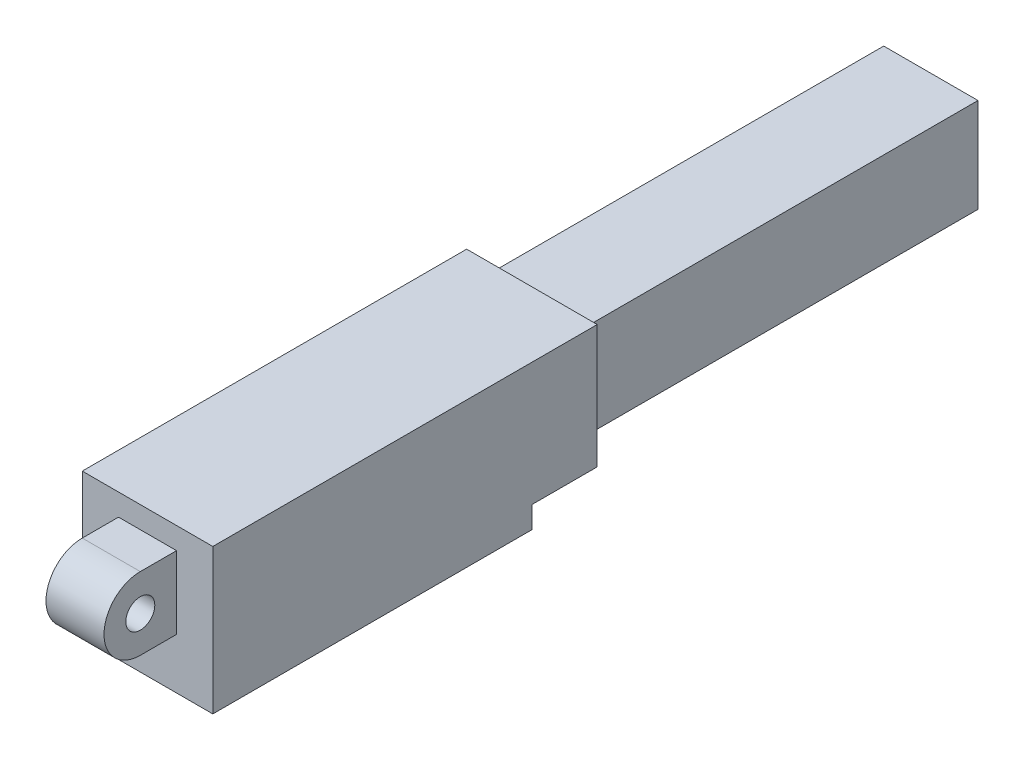
SolidWorks part; units mm, degrees
ref_plane "Front Plane" through (0, 0, 0) normal (0, 0, 1) x (1, 0, 0)
ref_plane "Top Plane" through (0, 0, 0) normal (0, 1, 0) x (1, 0, 0)
ref_plane "Right Plane" through (0, 0, 0) normal (1, 0, 0) x (0, 0, -1)
sketch "Sketch1" plane through (0, 0, 0) normal (1, 0, 0) x (0, 0, -1)
  line L0 (-26.5, 10) -> (26.5, 10)
  line L1 (26.5, 10) -> (26.5, -7)
  line L2 (26.5, -7) -> (17.5, -7)
  line L3 (17.5, -7) -> (17.5, -10)
  line L4 (17.5, -10) -> (-26.5, -10)
  line L5 (-26.5, -10) -> (-26.5, 10)
  line L6 (-26.5, -10) -> (26.5, 10) construction
  point P2 (0, 0)
  dimension "D1" = 53
  dimension "D2" = 20
  dimension "D3" = 9
  dimension "D4" = 3
extrude "Boss-Extrude1" add sketch "Sketch1" along normal mid plane 18
sketch "Sketch2" plane through (0, 0, 0) normal (1, 0, 0) x (0, 0, -1)
  line L0 (-31.5, 7) -> (-26.5, 7)
  line L1 (-26.5, 10) -> (-26.5, -10) construction
  line L2 (-26.5, 7) -> (-26.5, -3)
  line L3 (-26.5, -3) -> (-31.5, -3)
  line L4 (26.5, 10) -> (-26.5, 10) construction
  circle A0 centre (-31.5, 2) radius 2
  arc A1 (-31.5, 7) -> (-31.5, -3) centre (-31.5, 2) ccw
  dimension "D2" = 4
  dimension "D3" = 10
  dimension "D1" = 3
  dimension "D4" = 5
extrude "Boss-Extrude2" add sketch "Sketch2" along normal mid plane 8
sketch "Sketch3" plane through (0, 0, -26.5) normal (0, 0, -1) x (-1, 0, 0)
  line L0 (9, -7) -> (9, 10) construction
  line L1 (-6.5, -5) -> (6.5, -5)
  line L2 (-6.5, -5) -> (-6.5, 8)
  line L3 (-6.5, 8) -> (6.5, 8)
  line L4 (6.5, -5) -> (6.5, 8)
  line L5 (-6.5, -5) -> (6.5, 8) construction
  line L6 (-6.5, 8) -> (6.5, -5) construction
  line L7 (-9, 10) -> (9, 10) construction
  line L8 (-9, -7) -> (9, -7) construction
  point P0 (0, 1.5)
  dimension "D1" = 2.5
  dimension "D2" = 2
  dimension "D3" = 2
extrude "Boss-Extrude3" add sketch "Sketch3" along normal blind 55
sketch "Sketch4" plane through (0, 0, 0) normal (1, 0, 0) x (0, 0, -1)
  line L0 (-31.5, 2) -> (48.5, 2) construction
  line L1 (48.5, 8) -> (48.5, -5) construction
  line L2 (81.5, 8) -> (26.5, 8) construction
  line L3 (81.5, -5) -> (26.5, -5) construction
  dimension "D1" = 80
